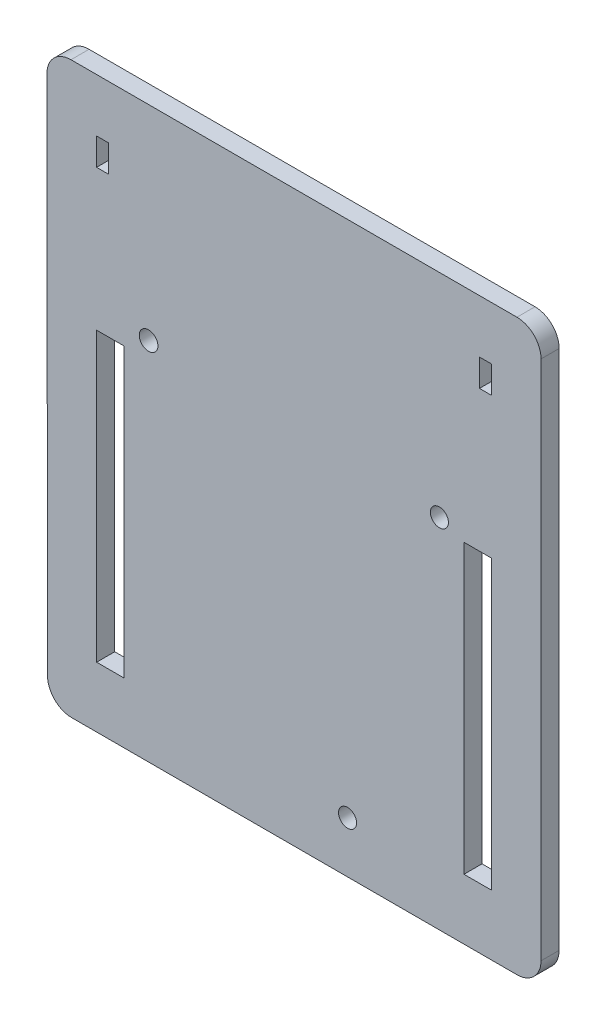
SolidWorks part; units mm, degrees
ref_plane "Plan de face" through (0, 0, 0) normal (0, 0, 1) x (1, 0, 0)
ref_plane "Plan de dessus" through (0, 0, 0) normal (0, 1, 0) x (1, 0, 0)
ref_plane "Plan de droite" through (0, 0, 0) normal (1, 0, 0) x (0, 0, -1)
sketch "Esquisse1" plane through (0, 0, 0) normal (0, 0, 1) x (1, 0, 0)
  line L0 (-41.0063, 88.5) -> (41.0063, 88.5)
  line L5 (41.0063, -6) -> (41.0063, 88.5)
  line L6 (-40.884, -6) -> (41.0063, -6)
  line L7 (-40.884, -6) -> (-41.0063, 88.5)
  line L9 (-32.7437, 51.76) -> (-28.2037, 51.76)
  line L10 (-32.7437, 51.76) -> (-32.7437, 4.04)
  line L12 (-32.7437, 4.04) -> (-28.2037, 4.04)
  line L13 (-28.2037, 51.76) -> (-28.2037, 4.04)
  line L14 (28.2163, 51.76) -> (32.7563, 51.76)
  line L15 (28.2163, 51.76) -> (28.2163, 4.04)
  line L16 (28.2163, 4.04) -> (32.7563, 4.04)
  line L17 (32.7563, 51.76) -> (32.7563, 4.04)
  line L22 (32.7563, 79.6656) -> (30.7907, 79.6656)
  line L23 (32.7563, 79.6656) -> (32.7563, 75.157)
  line L24 (32.7563, 75.157) -> (30.7907, 75.157)
  line L25 (30.7907, 79.6656) -> (30.7907, 75.157)
  line L28 (0, -55) -> (0, 55) construction
  line L29 (-32.7563, 75.157) -> (-30.7907, 75.157)
  line L30 (-30.7907, 79.6656) -> (-30.7907, 75.157)
  line L31 (-32.7563, 79.6656) -> (-30.7907, 79.6656)
  line L32 (-32.7563, 79.6656) -> (-32.7563, 75.157)
  circle A2 centre (8.8963, 2.5) radius 1.5
  circle A3 centre (-24.1237, 54.57) radius 1.5489
  circle A4 centre (24.1363, 53.3) radius 1.5
  circle A9 centre (31.7563, 78.7) radius 0.9656 construction
  circle A10 centre (31.771, 76.16) radius 1 construction
  circle A11 centre (-31.7563, 78.7) radius 0.9656 construction
  circle A12 centre (-31.771, 76.16) radius 1 construction
  point P22 (0, 0)
  point P23 (0, 0)
  point P24 (76.532, 73.1942)
  point P25 (76, 78.7795)
  point P26 (64.7532, 88.5)
  point P27 (0, 0)
  point P28 (69.9416, 3.4618)
  point P29 (0, 88.5)
  dimension "D4" = 3
  dimension "D7" = 3
  dimension "D18" = 9.8
  dimension "D16" = 8.25
  dimension "D10" = 94.5
  dimension "D2" = 16.8388
  dimension "D5" = 60.57
  dimension "D6" = 82.0127
  dimension "D8" = 47.72
  dimension "D9" = 48.26
  dimension "D11" = 8.5
  dimension "D13" = 49.7913
  dimension "D17" = 8.8344
  dimension "D19" = 10.04
  dimension "D21" = 10.04
  dimension "D22" = 8.1534
  dimension "D20" = 8.25
extrude "Boss.-Extru.1" add sketch "Esquisse1" along normal blind 3
fillet "Congé1" radius 4 4 edges at (41.0063, 88.5, 1.5) (41.0063, -6, 1.5) (-40.884, -6, 1.5) (-41.0063, 88.5, 1.5)
